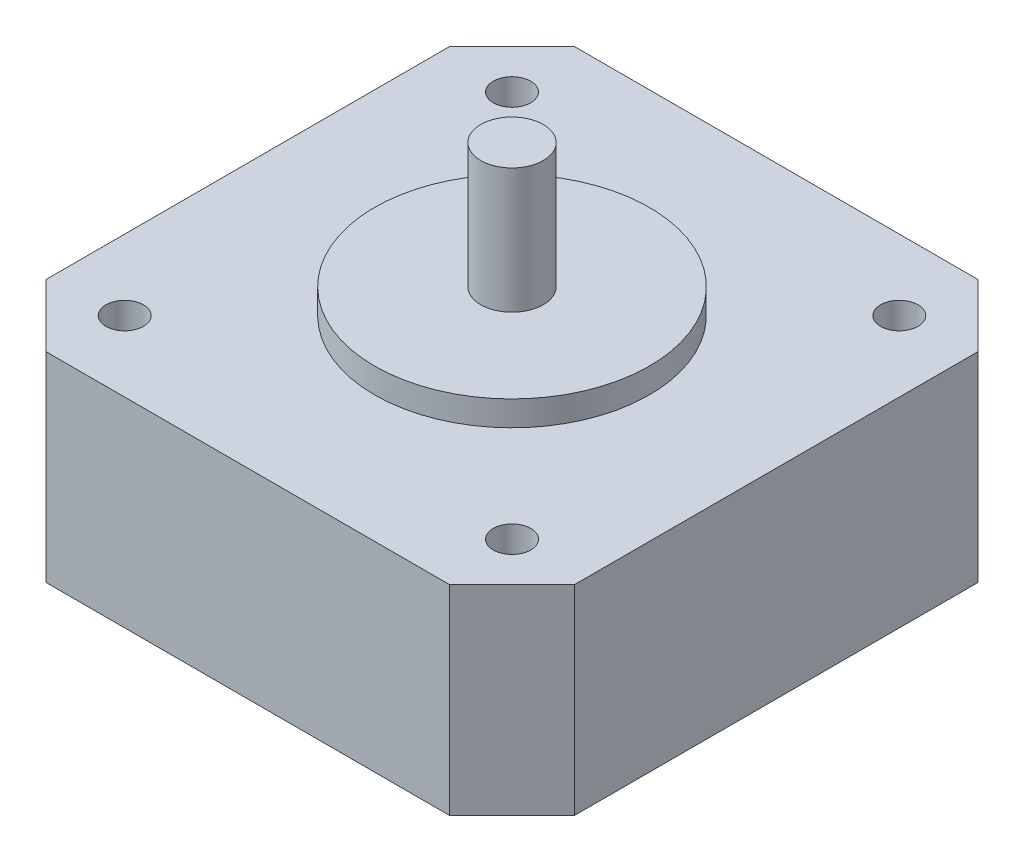
SolidWorks part; units mm, degrees
ref_plane "前视基准面" through (0, 0, 0) normal (0, 0, 1) x (1, 0, 0)
ref_plane "上视基准面" through (0, 0, 0) normal (0, 1, 0) x (1, 0, 0)
ref_plane "右视基准面" through (0, 0, 0) normal (1, 0, 0) x (0, 0, -1)
ref_plane "基准面1" through (0, -61.9, 0) normal (0, -1, 0) x (1, 0, 0)
sketch "草图1" plane through (0, -61.9, 0) normal (0, -1, 0) x (1, 0, 0)
  line L0 (21.15, -21.15) -> (21.15, 21.15)
  line L1 (21.15, 21.15) -> (-21.15, 21.15)
  line L2 (-21.15, 21.15) -> (-21.15, -21.15)
  line L3 (-21.15, -21.15) -> (21.15, -21.15)
extrude "凸台-拉伸1" add sketch "草图1" against normal blind 16
sketch "草图2" plane through (0, -45.9, 0) normal (0, 1, 0) x (-1, 0, 0)
  circle A0 centre (0, 0) radius 11
  dimension "D1" = 22
chamfer "倒角1" distance 5 angle 45 4 edges at (-21.15, -53.9, 21.15) (21.15, -53.9, 21.15) (-21.15, -53.9, -21.15) (21.15, -53.9, -21.15)
extrude "凸台-拉伸2" add sketch "草图2" along normal blind 2
sketch "草图3" plane through (0, -45.9, 0) normal (0, 1, 0) x (1, 0, 0)
  line L0 (-15.5, 15.5) -> (15.5, -15.5)
  line L1 (-15.5, -15.5) -> (15.5, 15.5)
  circle A0 centre (-15.5, 15.5) radius 1.5
  circle A1 centre (15.5, 15.5) radius 1.5
  circle A2 centre (15.5, -15.5) radius 1.5
  circle A3 centre (-15.5, -15.5) radius 1.5
  point P8 (0, 0)
  dimension "D1" = 3
  dimension "D2" = 3
  dimension "D3" = 3
  dimension "D4" = 3
  dimension "D5" = 31
  dimension "D6" = 31
extrude "切除-拉伸1" cut sketch "草图3" against normal blind 5
sketch "草图4" plane through (0, -43.9, 0) normal (0, 1, 0) x (1, 0, 0)
  circle A0 centre (0, 0) radius 2.5
  dimension "D1" = 5
extrude "凸台-拉伸3" add sketch "草图4" along normal blind 10 contours A0
